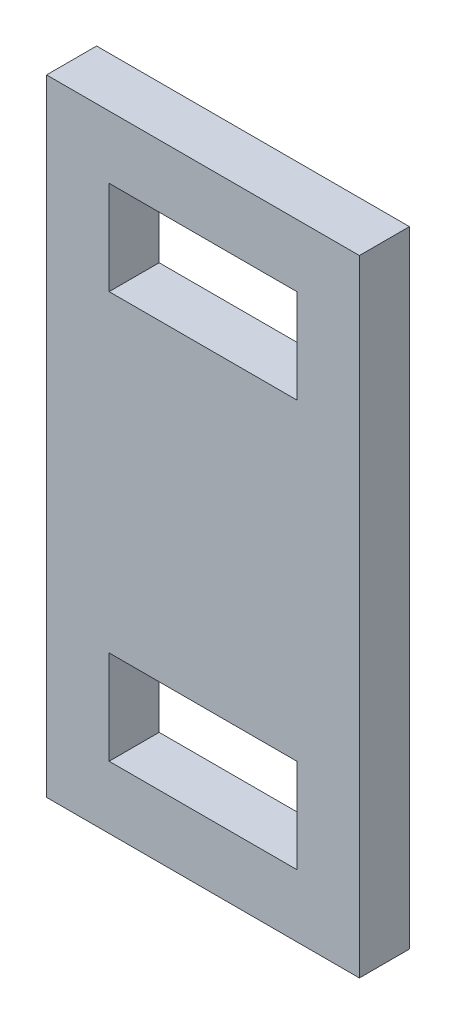
SolidWorks part; units mm, degrees
ref_plane "Plan de face" through (0, 0, 0) normal (0, 0, 1) x (1, 0, 0)
ref_plane "Plan de dessus" through (0, 0, 0) normal (0, 1, 0) x (1, 0, 0)
ref_plane "Plan de droite" through (0, 0, 0) normal (1, 0, 0) x (0, 0, -1)
sketch "Esquisse1" plane through (0, 0, 0) normal (0, 0, 1) x (1, 0, 0)
  line L0 (0, -5) -> (5, -5) construction
  line L1 (0, 0) -> (5, 0)
  line L2 (0, 0) -> (0, -10)
  line L3 (0, -10) -> (5, -10)
  line L4 (5, 0) -> (5, -10)
  line L5 (1, -7.5) -> (4, -7.5)
  line L6 (1, -7.5) -> (1, -9)
  line L7 (1, -9) -> (4, -9)
  line L8 (4, -7.5) -> (4, -9)
  line L9 (1, -1) -> (4, -1)
  line L10 (4, -2.5) -> (4, -1)
  line L11 (1, -2.5) -> (4, -2.5)
  line L12 (1, -2.5) -> (1, -1)
  dimension "D1" = 10
  dimension "D2" = 5
  dimension "D3" = 1
  dimension "D4" = 1.5
  dimension "D5" = 3
  dimension "D6" = 1
extrude "Boss.-Extru.1" add sketch "Esquisse1" along normal blind 0.8
